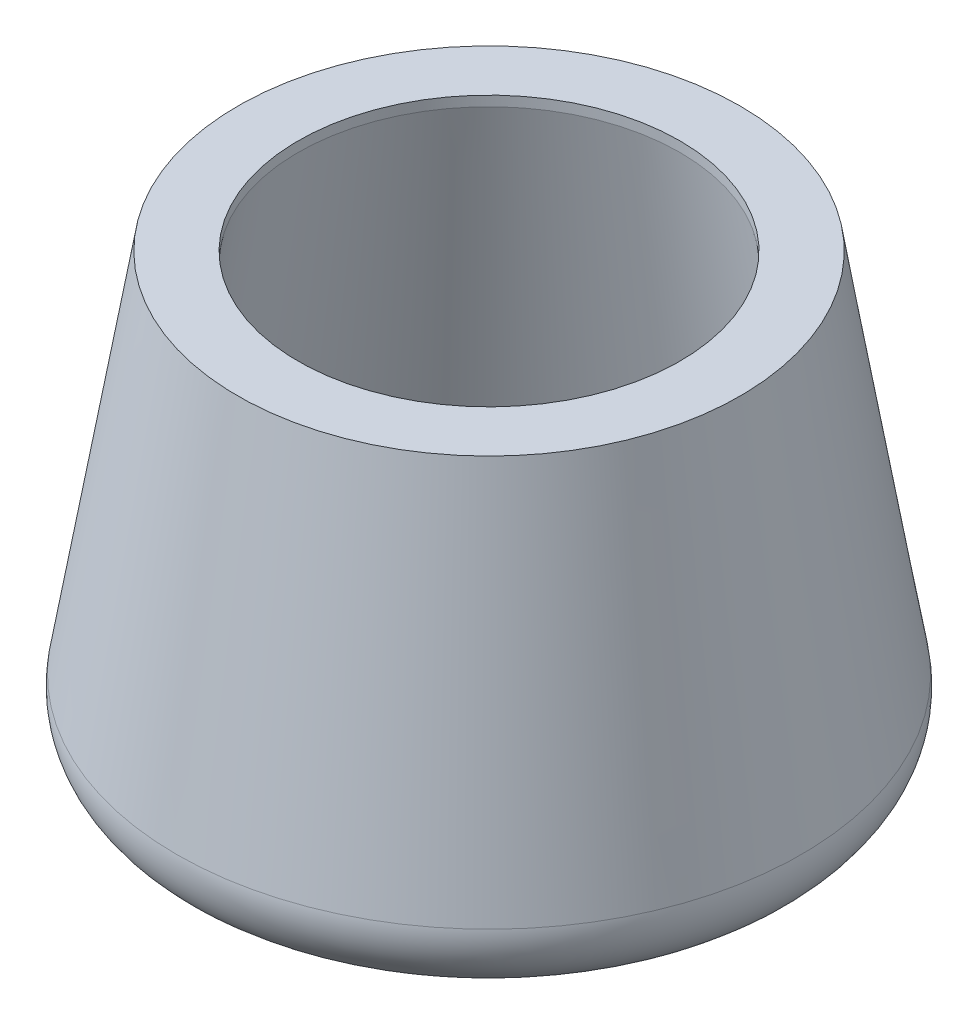
SolidWorks part; units mm, degrees
ref_plane "Front Plane" through (0, 0, 0) normal (0, 0, 1) x (1, 0, 0)
ref_plane "Top Plane" through (0, 0, 0) normal (0, 1, 0) x (1, 0, 0)
ref_plane "Right Plane" through (0, 0, 0) normal (1, 0, 0) x (0, 0, -1)
sketch "Sketch1" plane through (0, 0, 0) normal (0, 0, 1) x (1, 0, 0)
  line L0 (0, 0) -> (0, 15.24)
  line L1 (0, 15.24) -> (7.9375, 15.24)
  line L2 (7.9375, 15.24) -> (10.4775, 0)
  line L3 (10.4775, 0) -> (0, 0)
  line L4 (10.4429, 15.6576) -> (12.9829, 0.4176)
  line L5 (10.4775, -2.54) -> (0, -2.54)
  line L6 (10.4429, 15.6576) -> (13.4759, -2.54) construction
  line L7 (13.4759, -2.54) -> (0, -2.54) construction
  line L8 (10.4429, 15.6576) -> (7.9375, 15.6576)
  line L9 (7.9375, 15.6576) -> (7.9375, 15.24)
  line L10 (0, 0) -> (0, -2.54)
  arc A0 (12.9829, 0.4176) -> (10.4775, -2.54) centre (10.4775, 0) cw
  point P11 (0, 0)
  dimension "D5" = 2.54
  dimension "D1" = 7.9375
  dimension "D2" = 10.4775
  dimension "D3" = 15.24
  dimension "D4" = 2.54
revolve "Revolve1" add sketch "Sketch1" angle 360 about L0
